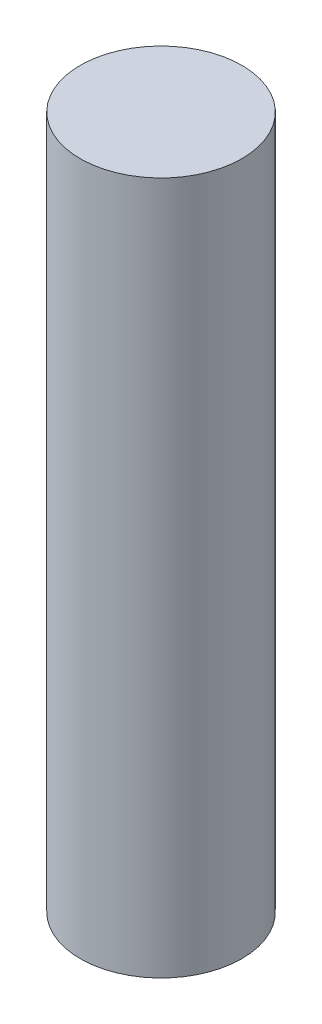
SolidWorks part; units mm, degrees
ref_plane "Ön Düzlem" through (0, 0, 0) normal (0, 0, 1) x (1, 0, 0)
ref_plane "Üst Düzlem" through (0, 0, 0) normal (0, 1, 0) x (1, 0, 0)
ref_plane "Sağ Düzlem" through (0, 0, 0) normal (1, 0, 0) x (0, 0, -1)
sketch "Sketch1" plane through (0, 0, 0) normal (0, 1, 0) x (1, 0, 0)
  circle A0 centre (0, 0) radius 5
extrude "Extrude-Thin2" add sketch "Sketch1" along normal blind 60 thin
sketch "Sketch2" plane through (0, 60, 0) normal (0, 1, 0) x (1, 0, 0)
  circle A0 centre (0, 0) radius 5
  dimension "D1" = 10
sketch "Sketch4" plane through (0, 0, 0) normal (0, -1, 0) x (1, 0, 0)
  circle A0 centre (0, 0) radius 5
  dimension "D1" = 10
extrude "Boss-Extrude4" add sketch "Sketch2" against normal blind 30 contours A0
